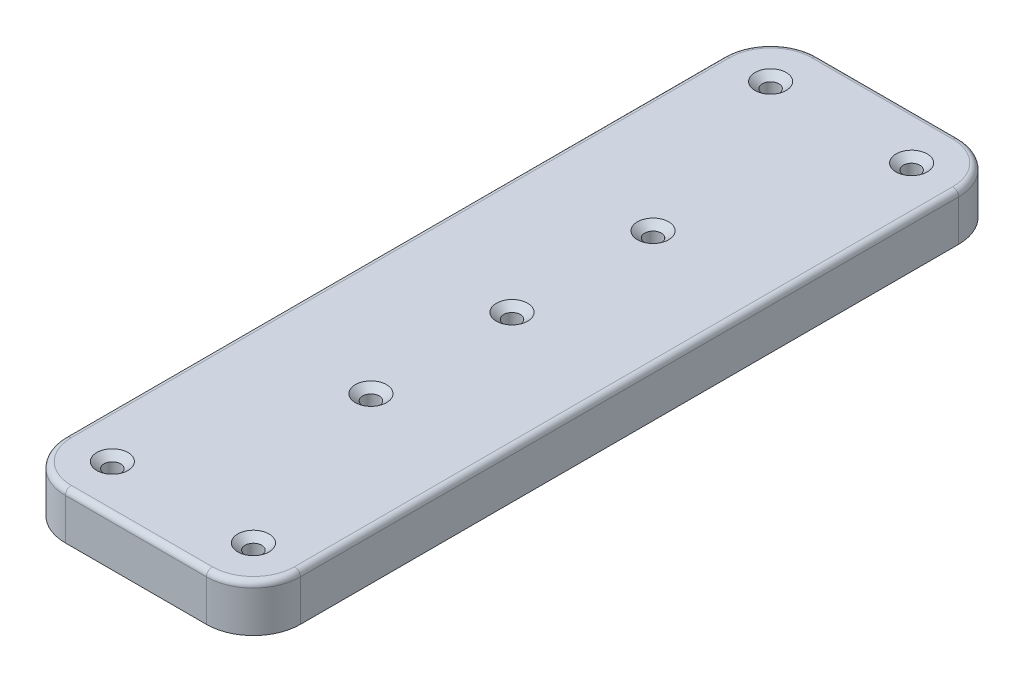
SolidWorks part; units mm, degrees
material "PE High Density"
ref_plane "Front Plane" through (0, 0, 0) normal (0, 0, 1) x (1, 0, 0)
ref_plane "Top Plane" through (0, 0, 0) normal (0, 1, 0) x (1, 0, 0)
ref_plane "Right Plane" through (0, 0, 0) normal (1, 0, 0) x (0, 0, -1)
sketch "Sketch1" plane through (0, 0, 0) normal (0, 0, 1) x (1, 0, 0)
  line L1 (-31.75, -6.35) -> (31.75, -6.35)
  line L2 (-31.75, -6.35) -> (-31.75, 6.35)
  line L3 (-31.75, 6.35) -> (31.75, 6.35)
  line L4 (31.75, -6.35) -> (31.75, 6.35)
  line L5 (-31.75, -6.35) -> (31.75, 6.35) construction
  line L6 (-31.75, 6.35) -> (31.75, -6.35) construction
  point P0 (0, 0)
  dimension "D1" = 12.7
  dimension "D2" = 63.5
extrude "Boss-Extrude1" add sketch "Sketch1" along normal mid plane 203.2
fillet "Fillet1" radius 12.7 4 edges at (-31.75, 0, -101.6) (31.75, 0, -101.6) (-31.75, 0, 101.6) (31.75, 0, 101.6)
hole_wizard "CSK for #8 Flat Head Machine Screw (100)1" positions "Sketch2" profile "Sketch3" countersink size "#8" standard "ANSI Inch" end condition through all
sketch "Sketch2" plane through (0, 6.35, 0) normal (0, 1, 0) x (1, 0, 0)
  point P0 (19.05, -88.9)
  point P3 (-19.05, -88.9)
  point P6 (-19.05, 88.9)
  point P9 (19.05, 88.9)
  point P13 (0, -38.1)
  point P15 (0, 38.1)
  point P25 (0, 0)
  dimension "D1" = 38.1
  dimension "D2" = 38.1
sketch "Sketch3" plane through (19.05, 6.35, 88.9) normal (1, 0, 0) x (0, 0, 1)
  line L0 (0, 0) -> (0, 12.7)
  line L1 (0, 12.7) -> (2.2479, 12.7)
  line L2 (2.2479, 12.7) -> (2.2479, 1.6518)
  line L3 (2.2479, 1.6518) -> (4.2164, 0)
  line L5 (4.2164, 0) -> (0, 0)
  line L6 (-2.2479, 1.6518) -> (-4.2164, 0) construction
  line L11 (0, -6.35) -> (0, 107.95) construction
  dimension "Thru Hole Dia." = 4.4958
  dimension "Thru Hole Depth" = 12.7
  dimension "Near C'Sink Dia." = 8.4328
  dimension "Near C'Sink Angle" = 100
fillet "Fillet2" radius 1.5875 8 edges at (-28.0303, 6.35, 97.8803) (0, 6.35, 101.6) (28.0303, 6.35, 97.8803) (31.75, 6.35, 0) (28.0303, 6.35, -97.8803) (0, 6.35, -101.6) (-28.0303, 6.35, -97.8803) (-31.75, 6.35, 0)
equation "\"D2@Sketch2\"=\"D1@Sketch2\""
